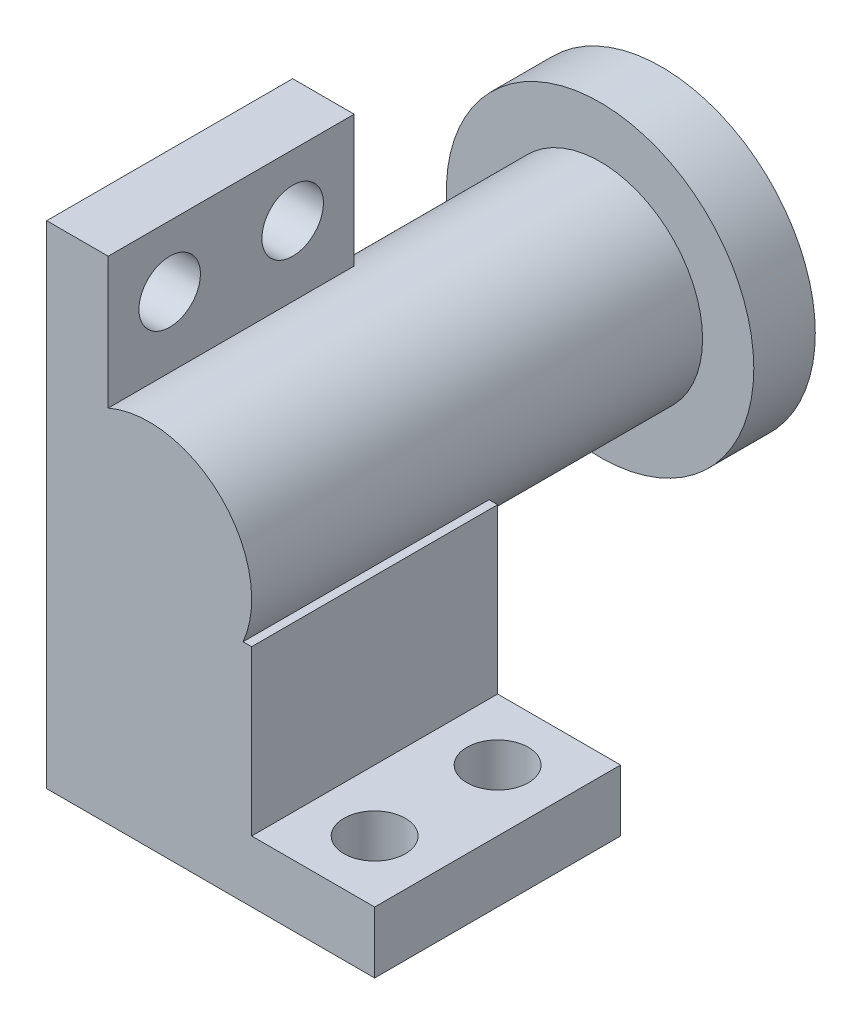
SolidWorks part; units mm, degrees
ref_plane "前视基准面" through (0, 0, 0) normal (0, 0, 1) x (1, 0, 0)
ref_plane "上视基准面" through (0, 0, 0) normal (0, 1, 0) x (1, 0, 0)
ref_plane "右视基准面" through (0, 0, 0) normal (1, 0, 0) x (0, 0, -1)
sketch "草图1" plane through (0, 0, 0) normal (0, 0, 1) x (1, 0, 0)
  line L0 (-5, 0) -> (-5, 11)
  line L1 (-5, 11) -> (-2, 11)
  line L2 (-2, 11) -> (-2, 4.5826)
  line L3 (0, -5) -> (11, -5)
  line L4 (-5, 0) -> (-5, -5)
  line L5 (-5, -5) -> (0, -5)
  line L6 (11, -5) -> (11, -2)
  line L7 (11, -2) -> (4.5826, -2)
  line L8 (11, -5) -> (11, -13)
  line L9 (11, -13) -> (-5, -13)
  line L10 (-5, -13) -> (-5, -5)
  line L11 (0, 0) -> (0, -13) construction
  arc A0 (4.5826, -2) -> (-2, 4.5826) centre (0, 0) ccw
extrude "凸台-拉伸1" add sketch "草图1" along normal blind 12 contours L7 A0 L2 L1 L0 L4 L5 L3 L6 | L10 L9 L8 L3 L5 | L11 L5 L10 L9
sketch "草图2" plane through (0, 0, 12) normal (0, 0, 1) x (1, 0, 0)
  circle A0 centre (0, 0) radius 5
extrude "凸台-拉伸2" add sketch "草图2" along normal blind 10
sketch "草图3" plane through (0, 0, 22) normal (0, 0, 1) x (1, 0, 0)
  circle A0 centre (0, 0) radius 7.5
extrude "凸台-拉伸3" add sketch "草图3" along normal blind 3
sketch "草图4" plane through (-2, 0, 0) normal (1, 0, 0) x (0, 0, -1)
  line L0 (-12, 11) -> (-12, 4.9971)
  line L2 (-12, 7.9985) -> (-9, 7.9985)
  line L3 (0, 7.9985) -> (-3, 7.9985)
  circle A0 centre (-9, 7.9985) radius 1.5
  circle A1 centre (-3, 7.9985) radius 1.5
extrude "切除-拉伸1" cut sketch "草图4" against normal blind 3
sketch "草图5" plane through (0, -2, 0) normal (0, 1, 0) x (1, 0, 0)
  line L0 (11, -12) -> (5, -12)
  line L1 (5, -22) -> (5, 0) construction
  line L3 (8, -12) -> (8, -9)
  line L4 (8, 0) -> (8, -3)
  circle A0 centre (8, -9) radius 1.5
  circle A1 centre (8, -3) radius 1.5
extrude "切除-拉伸2" cut sketch "草图5" against normal blind 11
sketch "草图6" plane through (0, -2, 0) normal (0, 1, 0) x (1, 0, 0)
  line L1 (5, 0) -> (11, 0)
  line L2 (5, 0) -> (5, -12)
  line L3 (5, -12) -> (11, -12)
  line L4 (11, 0) -> (11, -12)
extrude "切除-拉伸3" cut sketch "草图6" against normal blind 8
ref_plane "基准面1" through (11, 0, 0) normal (1, 0, 0) x (0, 0, -1)
mirror "镜向1" about plane through (0, 0, 25) normal (0, 0, 1) of bodies 106
delete or keep bodies "实体-删除/保留 2" type delete bodies bodies 106
